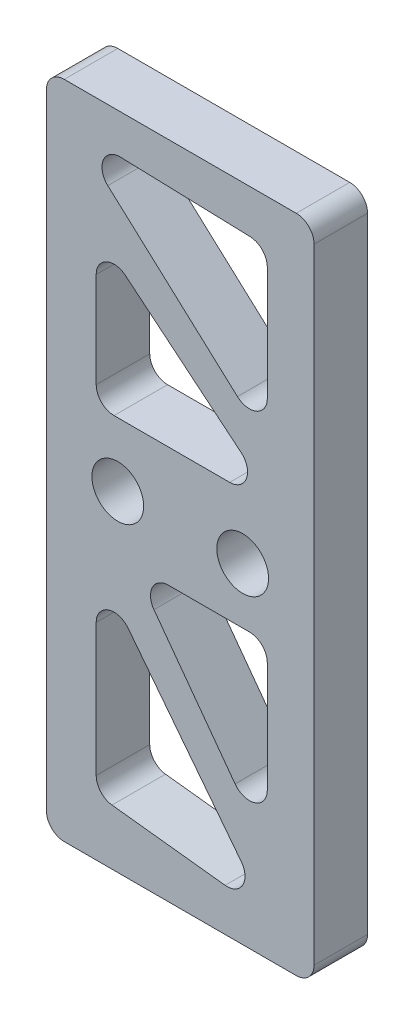
SolidWorks part; units mm, degrees
material "Thornel Mat VMA"
ref_plane "前视基准面" through (0, 0, 0) normal (0, 0, 1) x (1, 0, 0)
ref_plane "上视基准面" through (0, 0, 0) normal (0, 1, 0) x (1, 0, 0)
ref_plane "右视基准面" through (0, 0, 0) normal (1, 0, 0) x (0, 0, -1)
sketch "草图1" plane through (0, 0, 0) normal (0, 0, 1) x (1, 0, 0)
  line L0 (0, 0) -> (15, 0)
  line L1 (15, 0) -> (15, 37)
  line L3 (15, 37) -> (0, 37)
  line L4 (0, 37) -> (0, 0)
  circle A0 centre (4, 18.5) radius 1.45
  circle A1 centre (11, 18.5) radius 1.45
  dimension "D3" = 2.9
  dimension "D4" = 2.9
  dimension "D5" = 18.5
  dimension "D6" = 18.5
  dimension "D7" = 4
  dimension "D8" = 4
  dimension "D1" = 37
  dimension "D2" = 15
extrude "凸台-拉伸1" add sketch "草图1" along normal blind 3
sketch "草图2" plane through (0, 0, 3) normal (0, 0, 1) x (1, 0, 0)
  line L0 (1.4349, 34.8826) -> (12.3792, 34.5438)
  line L1 (12.3792, 34.5438) -> (12.3792, 24.9361)
  line L2 (12.3792, 24.9361) -> (1.4349, 34.8826)
  line L3 (2.7902, 30.5455) -> (2.7902, 22.0747)
  line L4 (2.7902, 22.0747) -> (13.0569, 22.0747)
  line L5 (13.0569, 22.0747) -> (2.7902, 30.5455)
  line L6 (4.8571, 15.3658) -> (12.3792, 15.3658)
  line L7 (12.3792, 15.3658) -> (12.3792, 5.133)
  line L8 (12.3792, 5.133) -> (4.8571, 15.3658)
  line L9 (2.7902, 14.4509) -> (2.7902, 3.2158)
  line L10 (2.7902, 3.2158) -> (12.3792, 2.1174)
  line L11 (12.3792, 2.1174) -> (2.7902, 14.4509)
  point P11 (10.2784, 3.5066)
  point P13 (3.2985, 3.2356)
  point P14 (12.3792, 5.133)
  point P15 (6.4496, 15.3319)
  point P16 (2.7902, 14.4509)
  point P17 (4.8571, 15.3658)
  point P18 (2.7902, 34.2388)
  point P19 (12.3792, 34.5438)
  point P20 (2.7902, 30.5455)
  point P21 (13.0569, 22.0747)
  point P22 (1.4349, 34.8826)
  point P23 (12.3792, 2.1174)
extrude "切除-拉伸1" cut sketch "草图2" against normal blind 10
fillet "圆角3" radius 1 16 edges at (15, 37, 1.5) (15, 0, 1.5) (0, 0, 1.5) (12.3792, 24.9361, 1.5) (12.3792, 34.5438, 1.5) (1.4349, 34.8826, 1.5) (2.7902, 14.4509, 1.5) (2.7902, 3.2158, 1.5) (12.3792, 2.1174, 1.5) (12.3792, 5.133, 1.5) (12.3792, 15.3658, 1.5) (4.8571, 15.3658, 1.5) (2.7902, 30.5455, 1.5) (2.7902, 22.0747, 1.5) (13.0569, 22.0747, 1.5) (0, 37, 1.5)
